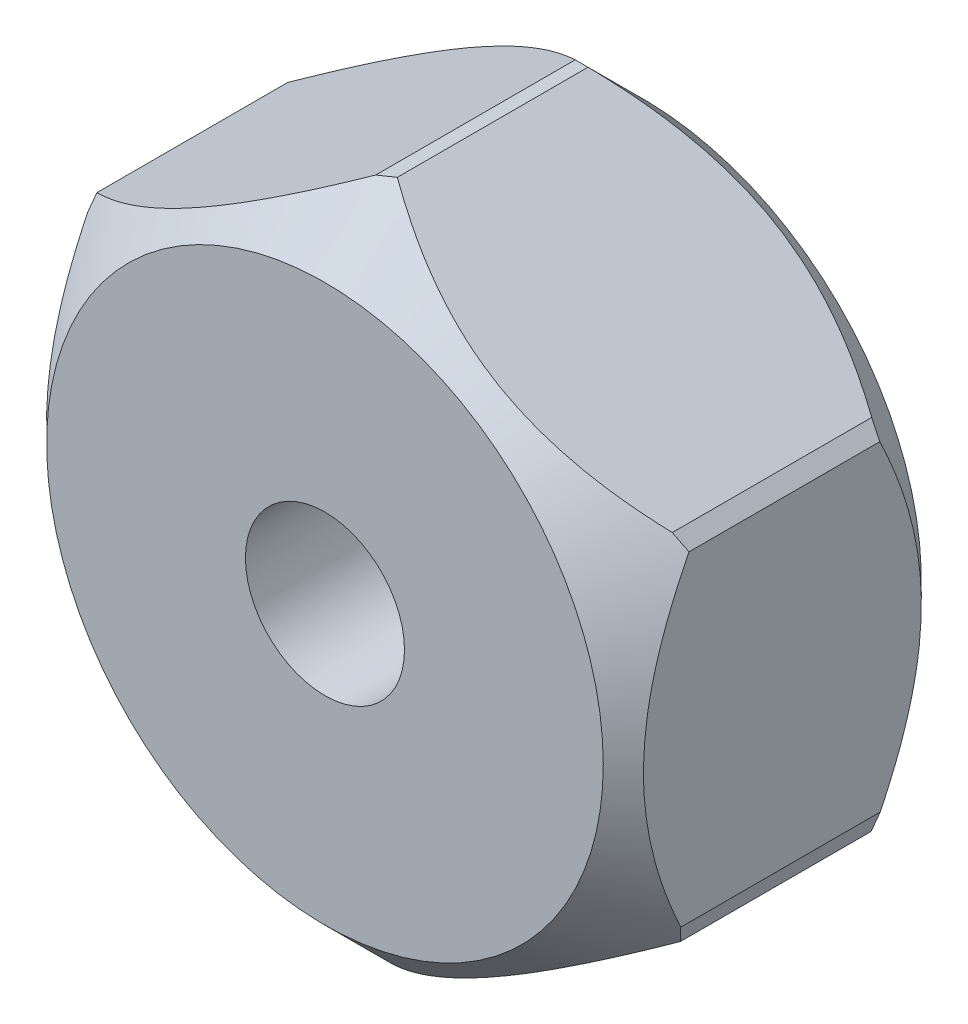
SolidWorks part; units mm, degrees
ref_plane "Front Plane" through (0, 0, 0) normal (0, 0, 1) x (1, 0, 0)
ref_plane "Top Plane" through (0, 0, 0) normal (0, 1, 0) x (1, 0, 0)
ref_plane "Right Plane" through (0, 0, 0) normal (1, 0, 0) x (0, 0, -1)
sketch "Sketch1" plane through (0, 0, 0) normal (0, 0, 1) x (1, 0, 0)
  line L1 (11.1807, -6.6345) -> (11.336, 6.3655)
  line L2 (11.336, 6.3655) -> (0.1553, 13)
  line L3 (0.1553, 13) -> (-11.1807, 6.6345)
  line L4 (-11.1807, 6.6345) -> (-11.336, -6.3655)
  line L5 (-11.336, -6.3655) -> (-0.1553, -13)
  line L6 (-0.1553, -13) -> (11.1807, -6.6345)
  circle A0 centre (0, 0) radius 11.2591 construction
  dimension "D1" = 26
extrude "Boss-Extrude1" add sketch "Sketch1" along normal blind 12
sketch "Sketch2" plane through (0, 0, 12) normal (0, 0, 1) x (1, 0, 0)
  circle A0 centre (0, 0) radius 10.5
  dimension "D1" = 21
extrude "Cut-Extrude1" cut sketch "Sketch2" against normal blind 10 draft 45 flip side to cut
sketch "Sketch3" plane through (0, 0, 0) normal (0, 0, -1) x (-1, 0, 0)
  circle A0 centre (0, 0) radius 10.5
  dimension "D1" = 21
extrude "Cut-Extrude2" cut sketch "Sketch3" against normal blind 10 draft 45 flip side to cut
chamfer "Chamfer2" distance 0.2 angle 45 6 edges at (11.336, 6.3655, 6) (0.1553, 13, 6) (-11.1807, 6.6345, 6) (-11.336, -6.3655, 6) (-0.1553, -13, 6) (11.1807, -6.6345, 6)
sketch "Sketch5" plane through (0, 0, 0) normal (0, 0, -1) x (-1, 0, 0)
  circle A0 centre (0, 0) radius 3
  dimension "D1" = 6
extrude "Cut-Extrude5" cut sketch "Sketch5" against normal blind 20
